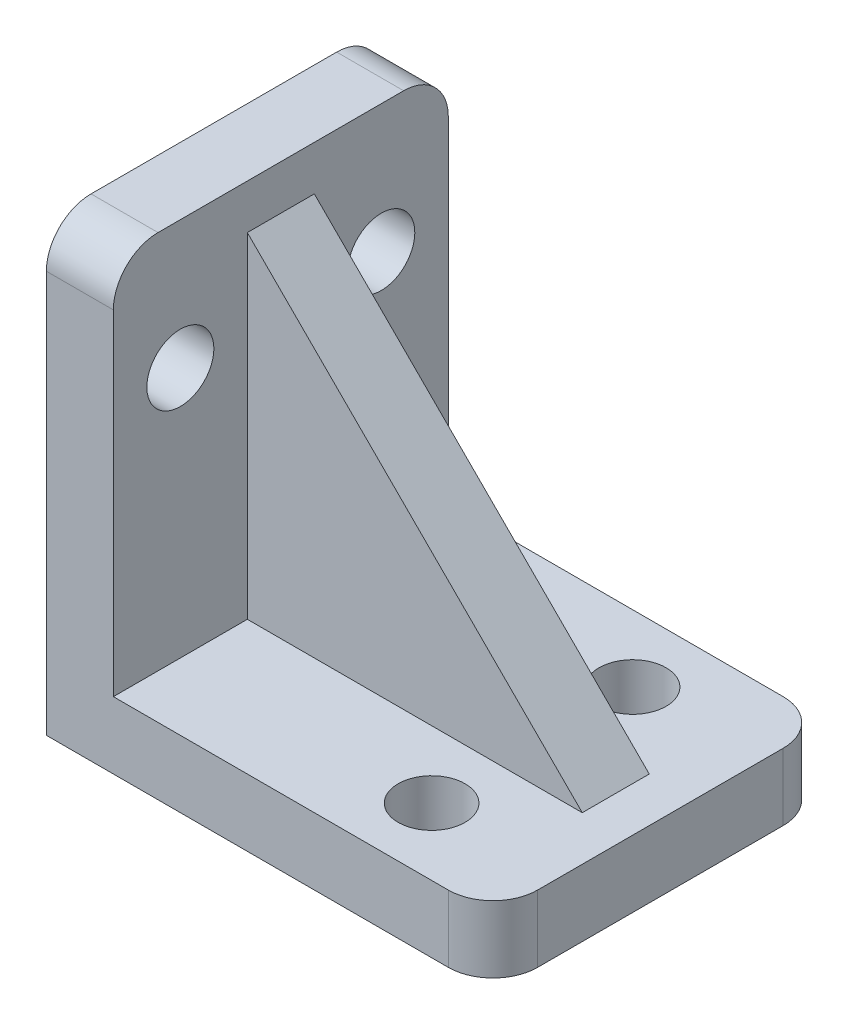
SolidWorks part; units mm, degrees
ref_plane "Front Plane" through (0, 0, 0) normal (0, 0, 1) x (1, 0, 0)
ref_plane "Top Plane" through (0, 0, 0) normal (0, 1, 0) x (1, 0, 0)
ref_plane "Right Plane" through (0, 0, 0) normal (1, 0, 0) x (0, 0, -1)
sketch "Sketch1" plane through (0, 0, 0) normal (0, 0, 1) x (1, 0, 0)
  line L0 (-7.6349, 12.3237) -> (-7.6349, -7.6763)
  line L1 (-7.6349, -7.6763) -> (12.3651, -7.6763)
  line L2 (12.3651, -7.6763) -> (12.3651, -4.6763)
  line L3 (12.3651, -4.6763) -> (-4.6349, -4.6763)
  line L4 (-4.6349, -4.6763) -> (-4.6349, 12.3237)
  line L5 (-4.6349, 12.3237) -> (-7.6349, 12.3237)
  dimension "D1" = 20
  dimension "D2" = 3
extrude "Boss-Extrude1" add sketch "Sketch1" along normal blind 15
other "Gusset1" parameters "D1"=3, "D2"=3, "D3"=0, "D4"=0, "D10"=5, "D11"=15, "D12"=15, "D13"=15, "D14"=45, "D15"=15
sketch "Sketch2" plane through (-4.6349, -4.6763, 7.5) normal (0, 0, -1) x (-1, 0, 0)
  line L0 (0, 0) -> (0, 15)
  line L1 (0, 0) -> (-15, 0)
  line L2 (0, 15) -> (-15, 0)
sketch "Sketch3" plane through (-4.6349, 0, 0) normal (1, 0, 0) x (0, 0, -1)
  line L0 (-9, 10.3237) -> (-9, -4.6763) construction
  line L1 (-9, 10.3237) -> (-9, -4.6763)
  line L2 (-6, 10.3237) -> (-6, -4.6763) construction
  line L3 (-6, 10.3237) -> (-6, -4.6763)
  line L4 (0, -4.6763) -> (0, 12.3237)
  line L5 (0, 12.3237) -> (-15, 12.3237)
  line L6 (-15, 12.3237) -> (-15, -4.6763)
  line L7 (-15, -4.6763) -> (0, -4.6763)
  line L8 (0, -4.6763) -> (0, 12.3237)
  line L9 (0, 12.3237) -> (-15, 12.3237)
  line L10 (-15, 12.3237) -> (-15, -4.6763)
  line L11 (-15, -4.6763) -> (0, -4.6763)
  line L12 (-9, 10.3237) -> (-15, 10.3237)
  line L13 (-12, 10.3237) -> (-12, 0.362) construction
  line L14 (-7.5, 10.3237) -> (-7.5, 15.637)
  line L15 (-6, 10.3237) -> (-9, 10.3237) construction
  circle A0 centre (-12, 6.5766) radius 1.5
  circle A2 centre (-3, 6.5766) radius 1.5
  dimension "D2" = 3
  dimension "D1" = 0
extrude "Cut-Extrude1" cut sketch "Sketch3" against normal blind 15 contours A0 L13 | L13 A0 | A2
sketch "Sketch4" plane through (0, -4.6763, 0) normal (0, 1, 0) x (1, 0, 0)
  line L0 (8.7444, -6) -> (-4.6349, -6)
  line L1 (10.3651, -9) -> (-4.6349, -9)
  line L2 (-4.6349, -15) -> (12.3651, -15)
  line L3 (12.3651, -15) -> (12.3651, 0)
  line L4 (12.3651, 0) -> (-4.6349, 0)
  line L5 (-4.6349, 0) -> (-4.6349, -15)
  line L6 (8.7444, -6) -> (8.7444, 0)
  line L7 (8.7444, -3) -> (0.4035, -3) construction
  line L8 (10.3651, -7.5) -> (15.6785, -7.5)
  circle A0 centre (6.6181, -3) radius 1.5
  circle A1 centre (6.6181, -12) radius 1.5
  dimension "D1" = 3
extrude "Cut-Extrude2" cut sketch "Sketch4" against normal blind 15 contours L7 A0 | A0 L7 | A1
fillet "Fillet1" radius 2 4 edges at (12.3651, -6.1763, 0) (12.3651, -6.1763, 15) (-6.1349, 12.3237, 15) (-6.1349, 12.3237, 0)
